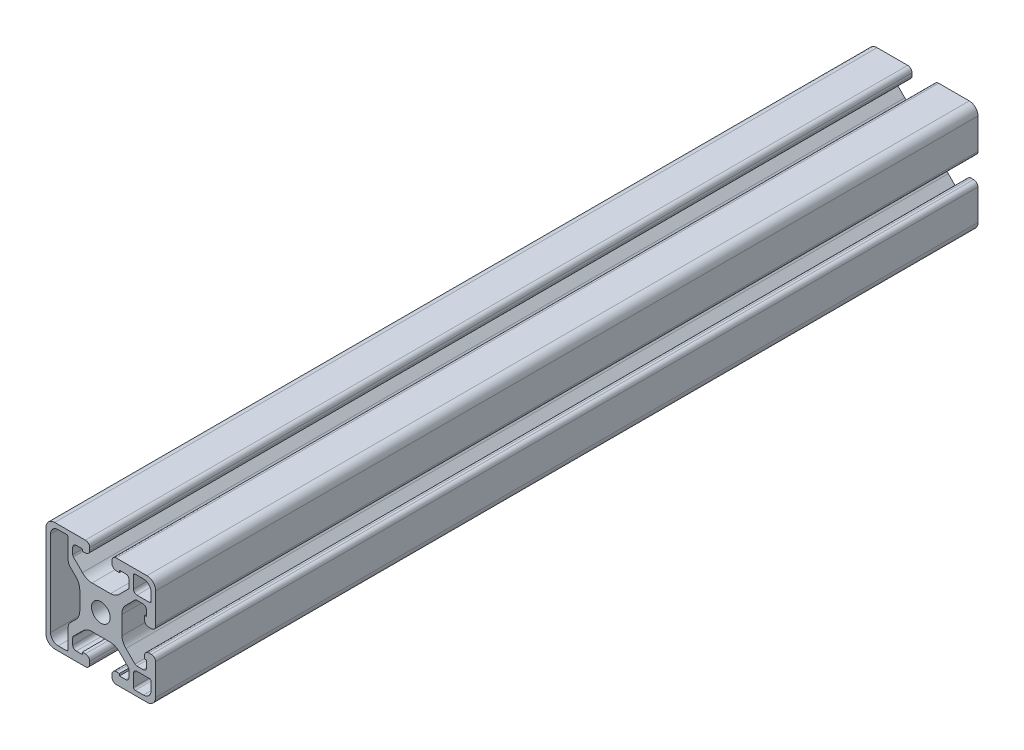
SolidWorks part; units mm, degrees
material "6105-T5 Aluminum"
ref_plane "Front Plane" through (0, 0, 0) normal (0, 0, 1) x (1, 0, 0)
ref_plane "Top Plane" through (0, 0, 0) normal (0, 1, 0) x (1, 0, 0)
ref_plane "Right Plane" through (0, 0, 0) normal (1, 0, 0) x (0, 0, -1)
sketch "Sketch1" plane through (0, 0, 0) normal (0, 0, 1) x (1, 0, 0)
  line L0 (0, 25.6796) -> (0, -24.255) construction
  line L1 (20.6348, 20.6348) -> (-21.6931, -21.6931) construction
  line L2 (0, 0) -> (23.6777, -23.6777) construction
  line L3 (11.9044, 17.715) -> (11.9044, 13.3034)
  line L4 (13.1744, 12.0334) -> (17.715, 12.0334)
  line L5 (18.35, 12.6684) -> (18.35, 15.556)
  line L6 (15.556, 18.35) -> (12.5394, 18.35)
  line L70 (-12.566, -18.35) -> (-15.556, -18.35)
  line L71 (-18.35, -15.5575) -> (-18.35, 15.5575)
  line L72 (-15.556, 18.35) -> (-12.566, 18.35)
  line L73 (-11.0096, 8.5897) -> (-9.0762, 6.6563)
  line L74 (-11.9311, 17.7218) -> (-11.9311, 10.9555)
  line L75 (-7.685, 3.2977) -> (-7.685, -3.4647)
  line L76 (-9.112, -6.8083) -> (-11.066, -8.7209)
  line L77 (-11.9311, -10.9555) -> (-11.9311, -17.7218)
  line L78 (15.556, -18.35) -> (12.5394, -18.35)
  line L79 (18.35, -12.6684) -> (18.35, -15.556)
  line L80 (13.1744, -12.0334) -> (17.715, -12.0334)
  line L81 (11.9044, -17.715) -> (11.9044, -13.3034)
  line L87 (-24.8341, 0) -> (22.8703, 0) construction
  line L88 (3.5467, 7.685) -> (-3.2157, 7.685)
  line L89 (-6.7073, 9.2147) -> (-9.9941, 12.5015)
  line L90 (-10.2545, 13.1301) -> (-10.2545, 15.4285)
  line L91 (-8.9845, 16.6985) -> (-6.7752, 16.6985)
  line L92 (-6.7752, 16.6985) -> (-6.7752, 15.936)
  line L93 (-6.7752, 15.936) -> (-5.6348, 15.936)
  line L94 (-4.06, 17.5108) -> (-4.06, 18.4252)
  line L95 (-5.6348, 20) -> (-13.0175, 20)
  line L96 (-13.0175, 20) -> (-16.825, 20)
  line L97 (-20, 16.825) -> (-20, -16.825)
  line L98 (-16.825, -20) -> (-13.0175, -20)
  line L99 (-13.0175, -20) -> (-5.6348, -20)
  line L100 (-4.06, -18.4252) -> (-4.06, -17.5108)
  line L101 (-5.6348, -15.936) -> (-6.7752, -15.936)
  line L102 (-6.7752, -15.936) -> (-6.7752, -16.6985)
  line L103 (-6.7752, -16.6985) -> (-8.9845, -16.6985)
  line L104 (-10.2545, -15.4285) -> (-10.2545, -13.1306)
  line L105 (-9.9941, -12.5019) -> (-6.7073, -9.2151)
  line L106 (-3.2152, -7.685) -> (3.3848, -7.685)
  line L107 (6.7926, -9.126) -> (9.994, -12.3275)
  line L108 (10.2544, -12.9561) -> (10.2544, -15.4395)
  line L109 (8.9845, -16.6985) -> (6.7752, -16.6985)
  line L110 (6.7752, -16.6985) -> (6.7752, -15.936)
  line L111 (6.7752, -15.936) -> (5.6348, -15.936)
  line L112 (4.06, -17.5108) -> (4.06, -18.4252)
  line L113 (5.6348, -20) -> (13.3417, -20)
  line L114 (13.3417, -20) -> (17.1517, -20)
  line L115 (20, -16.825) -> (20, -13.015)
  line L116 (20, -13.015) -> (20, -5.5728)
  line L117 (18.4264, -4.06) -> (17.5148, -4.06)
  line L118 (15.94, -5.6348) -> (15.94, -6.7752)
  line L119 (15.94, -6.7752) -> (16.7025, -6.7752)
  line L120 (16.7025, -6.7752) -> (16.7025, -8.9845)
  line L121 (15.383, -10.3834) -> (13.0851, -10.3834)
  line L122 (12.4565, -10.123) -> (9.1697, -6.8362)
  line L123 (7.685, -3.5711) -> (7.685, 3.1913)
  line L124 (8.9798, 6.6463) -> (12.2666, 9.9331)
  line L125 (13.0398, 10.3834) -> (15.3781, 10.3834)
  line L126 (16.6462, 9.1821) -> (16.6462, 6.9728)
  line L127 (16.6462, 6.9728) -> (15.94, 6.9728)
  line L128 (15.94, 6.9728) -> (15.94, 5.8324)
  line L129 (17.5024, 4.06) -> (18.4252, 4.06)
  line L130 (20, 5.6348) -> (20, 13.0142)
  line L131 (20, 13.0142) -> (20, 16.8242)
  line L132 (16.825, 20) -> (13.2905, 20)
  line L133 (13.2905, 20) -> (5.6348, 20)
  line L134 (4.06, 18.4252) -> (4.06, 17.5108)
  line L135 (5.6348, 15.936) -> (6.7752, 15.936)
  line L136 (6.7752, 15.936) -> (6.7752, 16.6985)
  line L137 (6.7752, 16.6985) -> (8.9845, 16.6985)
  line L138 (10.3155, 15.4299) -> (10.3155, 13.1309)
  line L139 (10.1069, 12.4403) -> (6.8256, 9.1591)
  arc A0 (13.1744, 12.0334) -> (11.9044, 13.3034) centre (13.1744, 13.3034) cw
  arc A1 (18.35, 12.6684) -> (17.715, 12.0334) centre (17.715, 12.6684) cw
  arc A2 (15.556, 18.35) -> (18.35, 15.556) centre (15.556, 15.556) cw
  arc A3 (11.9044, 17.715) -> (12.5394, 18.35) centre (12.5394, 17.715) cw
  circle A51 centre (0, 0) radius 3.4
  arc A52 (-12.566, -18.35) -> (-11.9311, -17.7218) centre (-12.566, -17.715) ccw
  arc A53 (-18.35, -15.5575) -> (-15.556, -18.35) centre (-15.556, -15.556) ccw
  arc A54 (-15.556, 18.35) -> (-18.35, 15.5575) centre (-15.556, 15.556) ccw
  arc A55 (-11.9311, 17.7218) -> (-12.566, 18.35) centre (-12.566, 17.715) ccw
  arc A56 (-11.9311, 10.9555) -> (-11.0096, 8.5897) centre (-8.7586, 10.8288) ccw
  arc A57 (-7.685, 3.2977) -> (-9.0762, 6.6563) centre (-12.4348, 3.2977) ccw
  arc A58 (-9.112, -6.8083) -> (-7.685, -3.4647) centre (-12.4345, -3.414) ccw
  arc A59 (-11.066, -8.7209) -> (-11.9311, -10.9555) centre (-8.7566, -10.8997) ccw
  arc A60 (11.9044, -17.715) -> (12.5394, -18.35) centre (12.5394, -17.715) ccw
  arc A61 (15.556, -18.35) -> (18.35, -15.556) centre (15.556, -15.556) ccw
  arc A62 (18.35, -12.6684) -> (17.715, -12.0334) centre (17.715, -12.6684) ccw
  arc A63 (13.1744, -12.0334) -> (11.9044, -13.3034) centre (13.1744, -13.3034) ccw
  arc A68 (-6.7073, 9.2147) -> (-3.2157, 7.685) centre (-3.2157, 12.4348) ccw
  arc A69 (-10.2545, 13.1301) -> (-9.9941, 12.5015) centre (-9.3655, 13.1301) ccw
  arc A70 (-8.9845, 16.6985) -> (-10.2545, 15.4285) centre (-8.9845, 15.4285) ccw
  arc A71 (-5.6348, 15.936) -> (-4.06, 17.5108) centre (-5.6348, 17.5108) ccw
  arc A72 (-4.06, 18.4252) -> (-5.6348, 20) centre (-5.6348, 18.4252) ccw
  arc A73 (-16.825, 20) -> (-20, 16.825) centre (-16.825, 16.825) ccw
  arc A74 (-20, -16.825) -> (-16.825, -20) centre (-16.825, -16.825) ccw
  arc A75 (-5.6348, -20) -> (-4.06, -18.4252) centre (-5.6348, -18.4252) ccw
  arc A76 (-4.06, -17.5108) -> (-5.6348, -15.936) centre (-5.6348, -17.5108) ccw
  arc A77 (-10.2545, -15.4285) -> (-8.9845, -16.6985) centre (-8.9845, -15.4285) ccw
  arc A78 (-9.9941, -12.5019) -> (-10.2545, -13.1306) centre (-9.3655, -13.1306) ccw
  arc A79 (-3.2152, -7.685) -> (-6.7073, -9.2151) centre (-3.2152, -12.4348) ccw
  arc A80 (6.7926, -9.126) -> (3.3848, -7.685) centre (3.3848, -12.4348) ccw
  arc A81 (10.2544, -12.9561) -> (9.994, -12.3275) centre (9.3654, -12.9561) ccw
  arc A82 (8.9845, -16.6985) -> (10.2544, -15.4395) centre (8.9845, -15.4285) ccw
  arc A83 (5.6348, -15.936) -> (4.06, -17.5108) centre (5.6348, -17.5108) ccw
  arc A84 (4.06, -18.4252) -> (5.6348, -20) centre (5.6348, -18.4252) ccw
  arc A85 (17.1517, -20) -> (20, -16.825) centre (16.825, -16.8418) ccw
  arc A86 (20, -5.5728) -> (18.4264, -4.06) centre (18.4264, -5.6348) ccw
  arc A87 (17.5148, -4.06) -> (15.94, -5.6348) centre (17.5148, -5.6348) ccw
  arc A88 (15.383, -10.3834) -> (16.7025, -8.9845) centre (15.4392, -9.1146) ccw
  arc A89 (12.4565, -10.123) -> (13.0851, -10.3834) centre (13.0851, -9.4944) ccw
  arc A90 (7.685, -3.5711) -> (9.1697, -6.8362) centre (12.4311, -3.3831) ccw
  arc A91 (8.9798, 6.6463) -> (7.685, 3.1913) centre (12.4309, 3.3829) ccw
  arc A92 (13.0398, 10.3834) -> (12.2666, 9.9331) centre (13.0398, 9.4944) ccw
  arc A93 (16.6462, 9.1821) -> (15.3781, 10.3834) centre (15.3781, 9.1134) ccw
  arc A94 (15.94, 5.8324) -> (17.5024, 4.06) centre (17.5024, 5.6348) ccw
  arc A95 (18.4252, 4.06) -> (20, 5.6348) centre (18.4252, 5.6348) ccw
  arc A96 (20, 16.8242) -> (16.825, 20) centre (16.825, 16.825) ccw
  arc A97 (5.6348, 20) -> (4.06, 18.4252) centre (5.6348, 18.4252) ccw
  arc A98 (4.06, 17.5108) -> (5.6348, 15.936) centre (5.6348, 17.5108) ccw
  arc A99 (10.3155, 15.4299) -> (8.9845, 16.6985) centre (9.0455, 15.4299) ccw
  arc A100 (10.1069, 12.4403) -> (10.3155, 13.1309) centre (9.4334, 13.0206) ccw
  arc A101 (3.5467, 7.685) -> (6.8256, 9.1591) centre (3.3834, 12.432) ccw
  dimension "D4" = 6.8
  dimension "D1" = 40
  dimension "D2" = 20
  dimension "D3" = 20.57
  dimension "D5" = 1.65
  dimension "D6" = 1.65
  dimension "D7" = 8.12
  dimension "D8" = 15.37
  dimension "D9" = 4.06
  dimension "D10" = 45
  dimension "D11" = 3.3
  dimension "D12" = 8.12
extrude "Extrude1" add sketch "Sketch1" against normal blind 300
